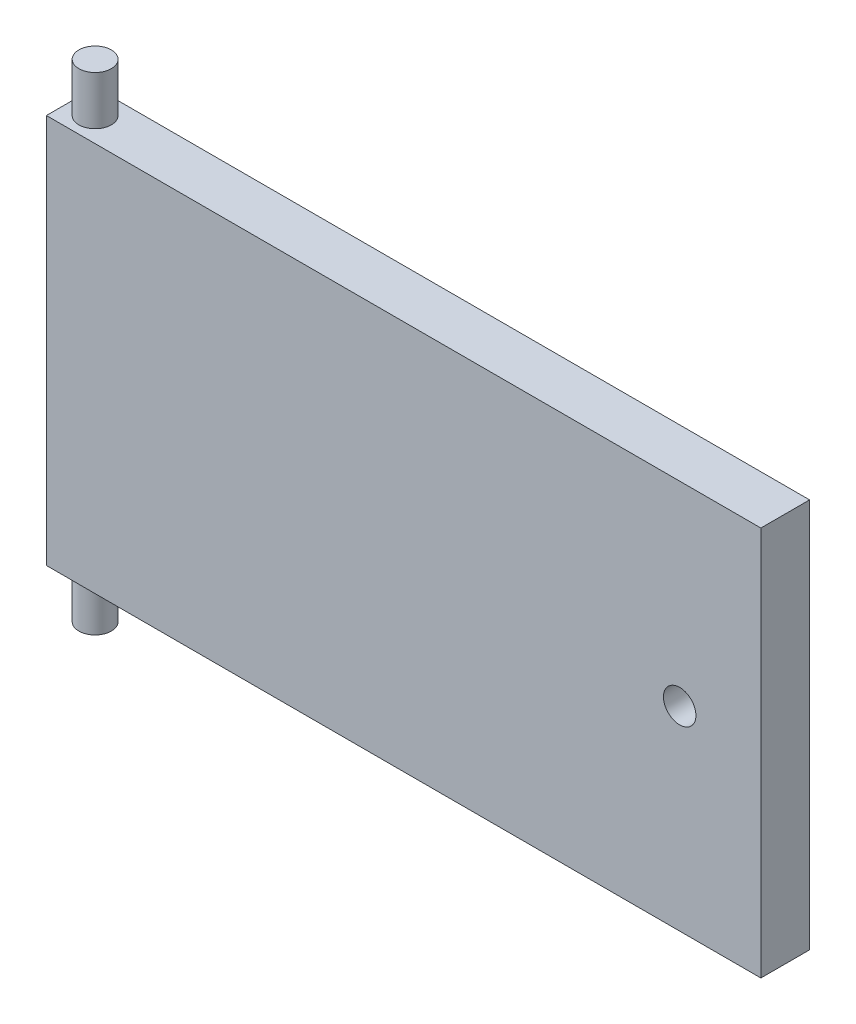
SolidWorks part; units mm, degrees
ref_plane "Front Plane" through (0, 0, 0) normal (0, 0, 1) x (1, 0, 0)
ref_plane "Top Plane" through (0, 0, 0) normal (0, 1, 0) x (1, 0, 0)
ref_plane "Right Plane" through (0, 0, 0) normal (1, 0, 0) x (0, 0, -1)
sketch "Sketch1" plane through (0, 0, 0) normal (0, 0, 1) x (1, 0, 0)
  line L1 (0, 0) -> (220, 0)
  line L2 (0, 0) -> (0, -120)
  line L3 (0, -120) -> (220, -120)
  line L4 (220, 0) -> (220, -120)
  dimension "D1" = 220
  dimension "D2" = 120
extrude "Boss-Extrude1" add sketch "Sketch1" along normal blind 15
sketch "Sketch2" plane through (0, 0, 0) normal (0, 1, 0) x (1, 0, 0)
  circle A0 centre (7.5, -7.5) radius 5
extrude "Boss-Extrude2" add sketch "Sketch2" along normal blind 15 and the other way blind 135
sketch "Sketch3" plane through (0, 0, 15) normal (0, 0, 1) x (1, 0, 0)
  line L0 (220, -120) -> (220, 0) construction
  circle A0 centre (195, -60) radius 5
  dimension "D1" = 25
extrude "Cut-Extrude1" cut sketch "Sketch3" against normal blind 25
